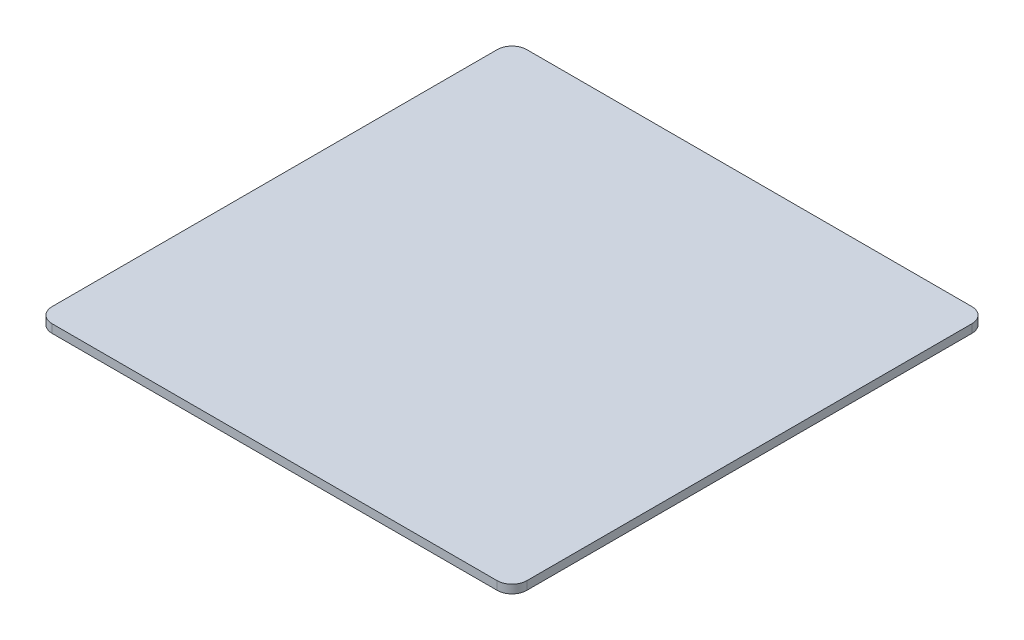
SolidWorks part; units mm, degrees
material "Thornel Mat VMA"
ref_plane "Front Plane" through (0, 0, 0) normal (0, 0, 1) x (1, 0, 0)
ref_plane "Top Plane" through (0, 0, 0) normal (0, 1, 0) x (1, 0, 0)
ref_plane "Right Plane" through (0, 0, 0) normal (1, 0, 0) x (0, 0, -1)
sketch "Sketch1" plane through (0, 0, 0) normal (0, 1, 0) x (1, 0, 0)
  line L1 (48, -48) -> (-48, -48)
  line L2 (48, -48) -> (48, 48)
  line L3 (48, 48) -> (-48, 48)
  line L4 (-48, -48) -> (-48, 48)
  line L5 (48, -48) -> (-48, 48) construction
  line L6 (48, 48) -> (-48, -48) construction
  point P0 (0, 0)
  dimension "D1" = 96
  dimension "D2" = 96
extrude "Boss-Extrude1" add sketch "Sketch1" along normal blind 1.7
fillet "Fillet1" radius 3 4 edges at (48, 0.85, 48) (48, 0.85, -48) (-48, 0.85, -48) (-48, 0.85, 48)
